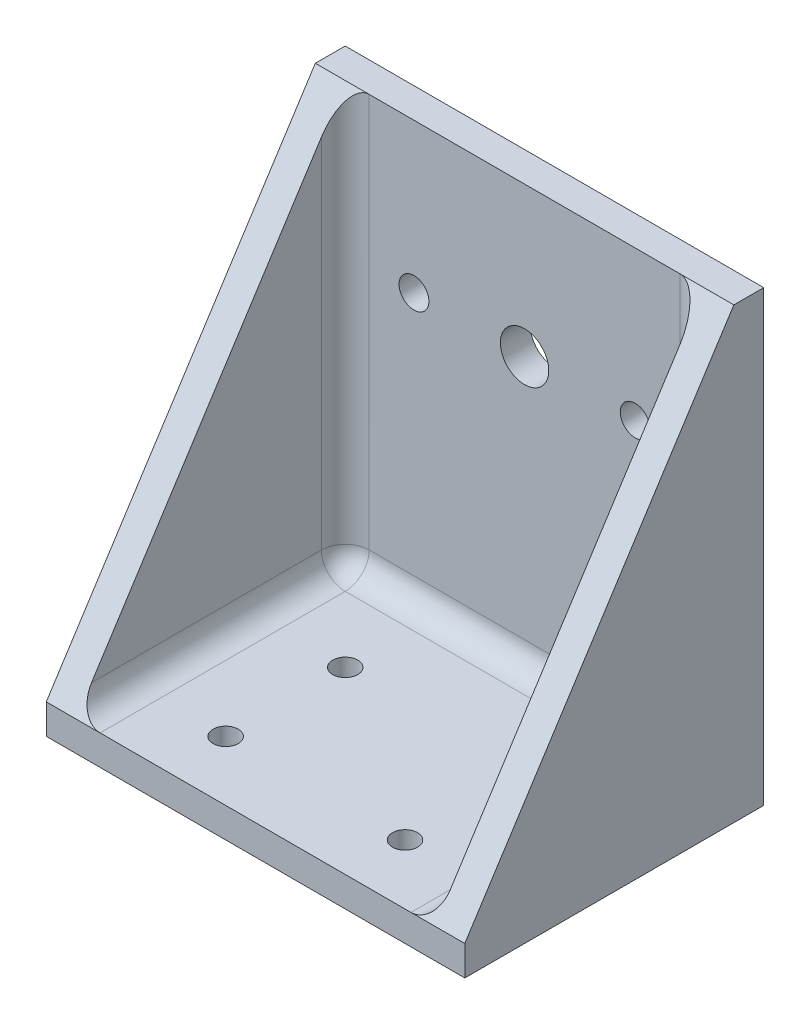
SolidWorks part; units mm, degrees
ref_plane "Front Plane" through (0, 0, 0) normal (0, 0, 1) x (1, 0, 0)
ref_plane "Top Plane" through (0, 0, 0) normal (0, 1, 0) x (1, 0, 0)
ref_plane "Right Plane" through (0, 0, 0) normal (1, 0, 0) x (0, 0, -1)
sketch "Sketch1" plane through (0, 0, 0) normal (0, 1, 0) x (1, 0, 0)
  line L1 (-35, -25) -> (35, -25)
  line L2 (-35, -25) -> (-35, 25)
  line L3 (-35, 25) -> (35, 25)
  line L4 (35, -25) -> (35, 25)
  line L5 (-35, -25) -> (35, 25) construction
  line L6 (-35, 25) -> (35, -25) construction
  point P0 (0, 0)
  dimension "D1" = 50
  dimension "D2" = 70
extrude "Boss-Extrude1" add sketch "Sketch1" along normal blind 5
sketch "Sketch2" plane through (0, 5, 0) normal (0, 1, 0) x (1, 0, 0)
  line L0 (35, -25) -> (35, 25) construction
  line L1 (-35, 25) -> (35, 25)
  line L2 (-35, 25) -> (-35, 20)
  line L3 (-35, 20) -> (35, 20)
  line L4 (35, 25) -> (35, 20)
  dimension "D1" = 5
extrude "Boss-Extrude2" add sketch "Sketch2" along normal blind 70
sketch "Sketch3" plane through (0, 0, -25) normal (0, 0, -1) x (-1, 0, 0)
  line L0 (-35, 0) -> (35, 0) construction
  circle A0 centre (0, 50) radius 4.05
  dimension "D1" = 50
  dimension "D2" = 8.1
extrude "Cut-Extrude1" cut sketch "Sketch3" against normal blind 10
sketch "Sketch4" plane through (0, 0, -25) normal (0, 0, -1) x (-1, 0, 0)
  line L0 (-18.5, 50) -> (18.5, 50) construction
  line L1 (-35, 0) -> (35, 0) construction
  circle A1 centre (-18.5, 50) radius 2.5
  circle A2 centre (18.5, 50) radius 2.5
  point P4 (0, 50)
  dimension "D3" = 5
  dimension "D4" = 5
  dimension "D1" = 18.5
  dimension "D2" = 50
extrude "Cut-Extrude2" cut sketch "Sketch4" against normal blind 10
sketch "Sketch5" plane through (35, 0, 0) normal (1, 0, 0) x (0, 0, -1)
  line L0 (20, 75) -> (-25, 5)
  line L1 (-25, 5) -> (20, 5)
  line L2 (20, 5) -> (20, 75)
extrude "Boss-Extrude3" add sketch "Sketch5" against normal blind 5
sketch "Sketch6" plane through (-35, 0, 0) normal (-1, 0, 0) x (0, 0, 1)
  line L0 (-20, 75) -> (25, 5)
  line L1 (25, 5) -> (-20, 5)
  line L2 (-20, 5) -> (-20, 75)
extrude "Boss-Extrude4" add sketch "Sketch6" against normal blind 5
fillet "Fillet1" radius 4 5 edges at (30, 40, -20) (30, 5, 2.5) (-30, 5, 2.5) (-30, 40, -20) (0, 5, -20)
sketch "Sketch7" plane through (0, 5, 0) normal (0, 1, 0) x (1, 0, 0)
  line L0 (-26, -25) -> (26, -25) construction
  line L1 (-26, 16) -> (-26, -25) construction
  circle A0 centre (-15, 5) radius 2.1
  circle A1 centre (15, 5) radius 2.1
  circle A2 centre (15, -15) radius 2.1
  circle A3 centre (-15, -15) radius 2.1
  dimension "D1" = 4.2
  dimension "D2" = 30
  dimension "D3" = 11
  dimension "D4" = 2
  dimension "D5" = 2
extrude "Cut-Extrude3" cut sketch "Sketch7" against normal blind 5
